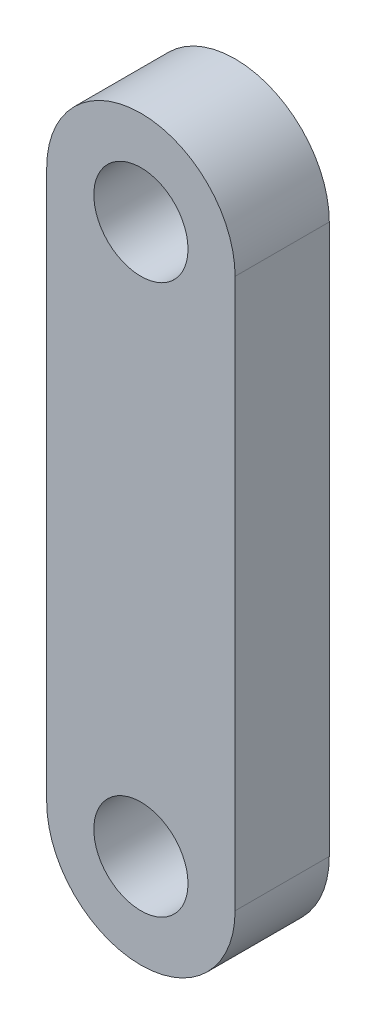
SolidWorks part; units mm, degrees
ref_plane "Front Plane" through (0, 0, 0) normal (0, 0, 1) x (1, 0, 0)
ref_plane "Top Plane" through (0, 0, 0) normal (0, 1, 0) x (1, 0, 0)
ref_plane "Right Plane" through (0, 0, 0) normal (1, 0, 0) x (0, 0, -1)
sketch "Sketch1" plane through (0, 0, 0) normal (0, 0, 1) x (1, 0, 0)
  line L0 (0, 17.5) -> (0, -17.5) construction
  line L1 (6, 17.5) -> (6, -17.5)
  line L2 (-6, 17.5) -> (-6, -17.5)
  arc A0 (6, 17.5) -> (-6, 17.5) centre (0, 17.5) ccw
  arc A1 (-6, -17.5) -> (6, -17.5) centre (0, -17.5) ccw
  circle A2 centre (0, 17.5) radius 3
  circle A3 centre (0, -17.5) radius 3
  point P2 (0, 0)
  dimension "D2" = 6
  dimension "D3" = 6
  dimension "D4" = 6
  dimension "D1" = 35
extrude "Boss-Extrude1" add sketch "Sketch1" against normal blind 6
scale "Scale1" scale about centroid uniform scaling yes scale factor 0.5
